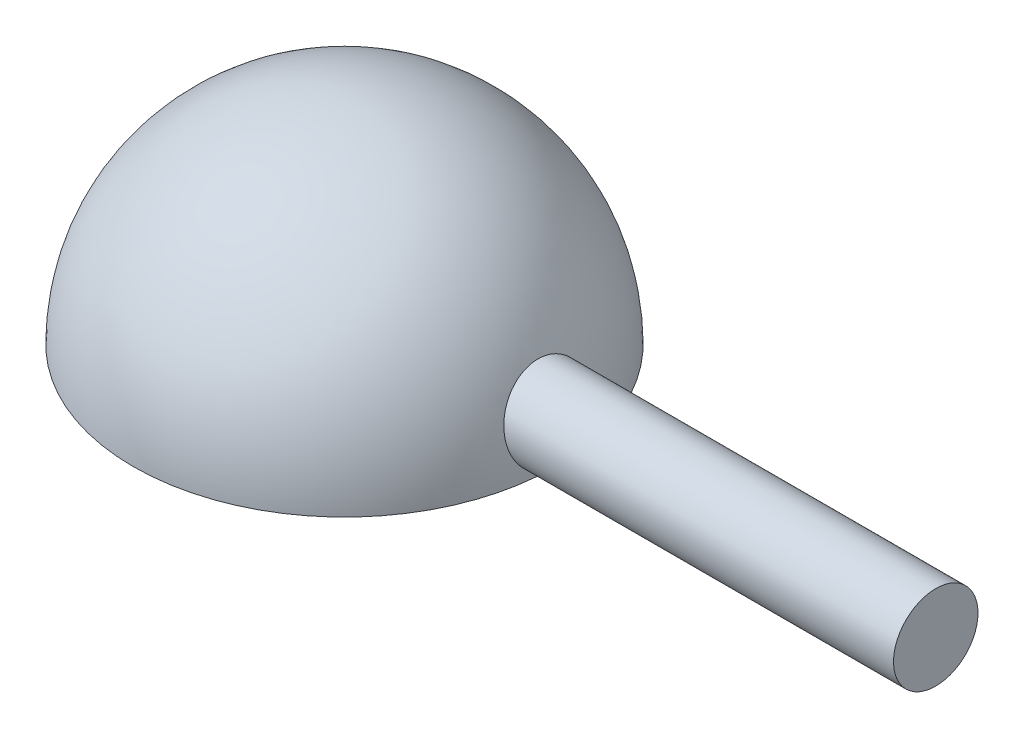
SolidWorks part; units mm, degrees
ref_plane "Front Plane" through (0, 0, 0) normal (0, 0, 1) x (1, 0, 0)
ref_plane "Top Plane" through (0, 0, 0) normal (0, 1, 0) x (1, 0, 0)
ref_plane "Right Plane" through (0, 0, 0) normal (1, 0, 0) x (0, 0, -1)
sketch "boog" plane through (0, 0, 0) normal (0, 0, 1) x (1, 0, 0)
  line L0 (-25, 0) -> (-22, 0)
  line L2 (0, 0) -> (0, 22) construction
  line L3 (0, 22) -> (0, 25)
  arc A0 (0, 22) -> (-22, 0) centre (0, 0) ccw
  arc A1 (0, 25) -> (-25, 0) centre (0, 0) ccw
  dimension "D1" = 3
  dimension "D2" = 25
revolve "bol_half" add sketch "boog" angle 360 about L2
ref_plane "Plane1" through (25, 0, 0) normal (1, 0, 0) x (0, 0, -1)
sketch "cirkel" plane through (25, 0, 0) normal (1, 0, 0) x (0, 0, -1)
  line L0 (-25, 0) -> (25, 0) construction
  line L1 (0, 0) -> (0, 5) construction
  circle A0 centre (0, 5) radius 5
  dimension "D1" = 10
extrude "arm" add sketch "cirkel" along normal blind 45 and the other way up to next
